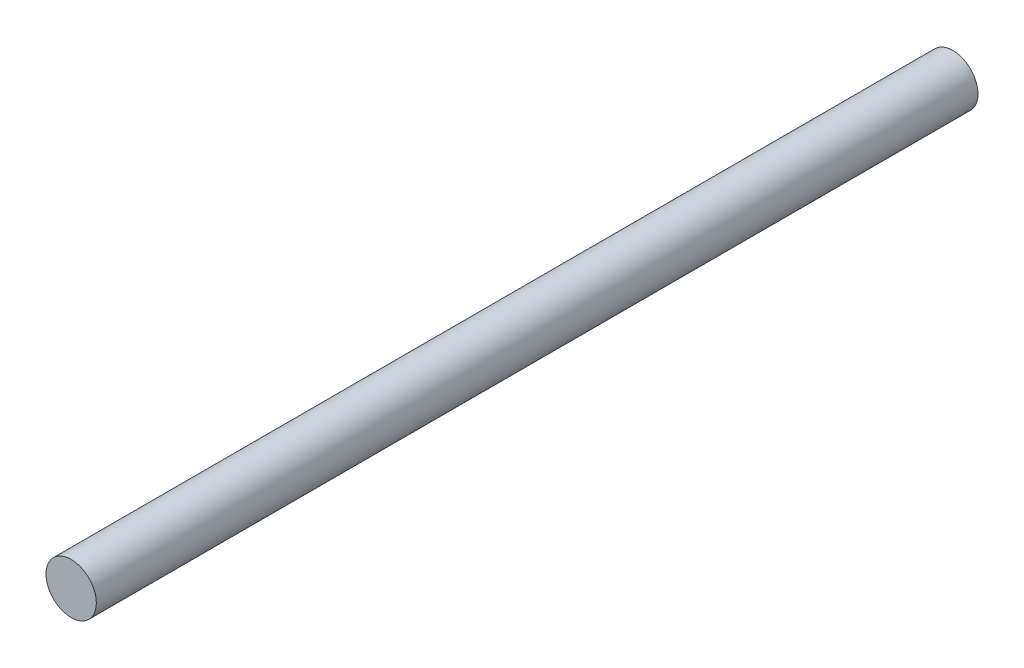
SolidWorks part; units mm, degrees
ref_plane "Front Plane" through (0, 0, 0) normal (0, 0, 1) x (1, 0, 0)
ref_plane "Top Plane" through (0, 0, 0) normal (0, 1, 0) x (1, 0, 0)
ref_plane "Right Plane" through (0, 0, 0) normal (1, 0, 0) x (0, 0, -1)
sketch "Sketch1" plane through (0, 0, 0) normal (0, 0, 1) x (1, 0, 0)
  circle A0 centre (0, 0) radius 1
extrude "Boss-Extrude1" add sketch "Sketch1" along normal mid plane 35
